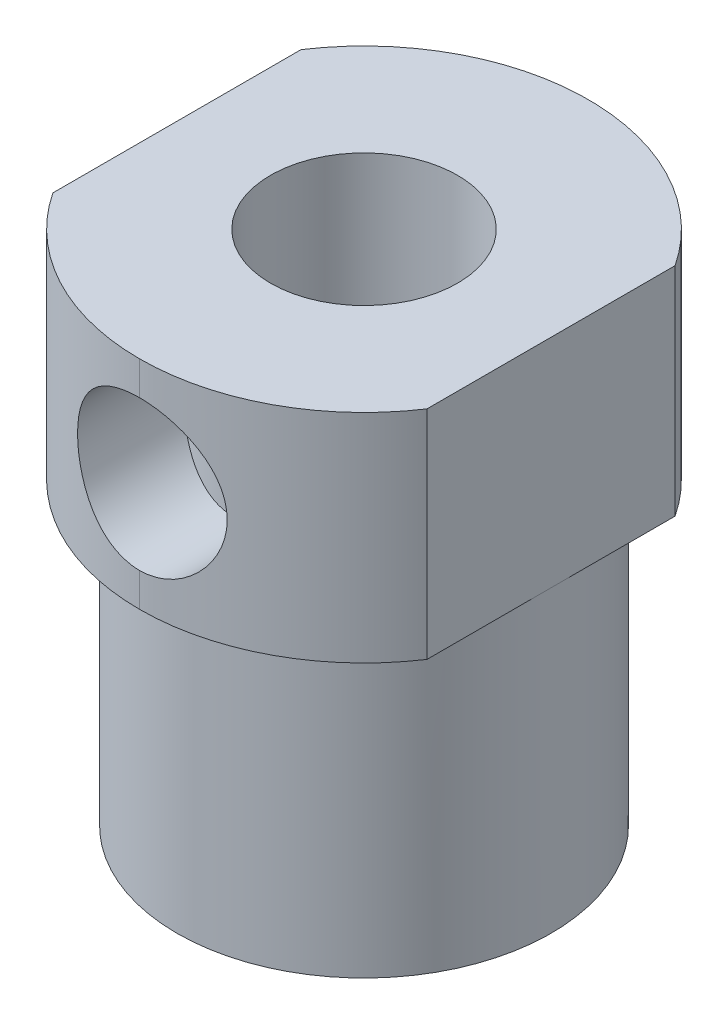
SolidWorks part; units mm, degrees
material "ABS"
ref_plane "Front Plane" through (0, 0, 0) normal (0, 0, 1) x (1, 0, 0)
ref_plane "Top Plane" through (0, 0, 0) normal (0, 1, 0) x (1, 0, 0)
ref_plane "Right Plane" through (0, 0, 0) normal (1, 0, 0) x (0, 0, -1)
sketch "Sketch4" plane through (0, 0, 0) normal (1, 0, 0) x (0, 0, -1)
  line L0 (-2.4, 0) -> (-2.4, 3)
  line L1 (-2.4, 3) -> (-0.75, 3)
  line L2 (-0.75, 3) -> (-0.75, 5)
  line L3 (-0.75, 5) -> (-2.5, 5)
  line L4 (-2.5, 5) -> (-2.5, 13.8)
  line L5 (-2.5, 13.8) -> (-6, 13.8)
  line L6 (-6, 13.8) -> (-6, 8)
  line L7 (-6, 8) -> (-5, 8)
  line L8 (-5, 8) -> (-5, 0)
  line L9 (-5, 0) -> (-2.4, 0)
  dimension "D1" = 3
  dimension "D2" = 2.4
  dimension "D3" = 5
  dimension "D4" = 0.75
  dimension "D5" = 8
  dimension "D6" = 6
  dimension "D7" = 5.8
  dimension "D8" = 2
  dimension "D9" = 2.5
sketch "Sketch2" plane through (0, 0, 0) normal (0, 1, 0) x (1, 0, 0)
  circle A0 centre (0, 0) radius 5
  dimension "D1" = 10
sweep "Sweep1" add profiles "Sketch4" path "Sketch2"
ref_plane "Plane1" through (0, 13.8, 6) normal (0, 0, 1) x (1, 0, 0)
sketch "Sketch5" plane through (0, 13.8, 6) normal (0, 0, 1) x (1, 0, 0)
  line L1 (0, 0) -> (0, -5.8) construction
  circle A0 centre (0, -2.9) radius 2
  dimension "D1" = 4
extrude "Cut-Extrude1" cut sketch "Sketch5" against normal offset from surface (3.1277 mm away) 1
sketch "Sketch7" plane through (0, 13.8, 0) normal (0, 1, 0) x (1, 0, 0)
  line L1 (-5, 6) -> (5, 6) construction
  line L2 (-5, 6) -> (-5, -6) construction
  line L3 (-5, -6) -> (5, -6) construction
  line L4 (5, 6) -> (5, -6) construction
  line L5 (-5, 6) -> (-6, 6)
  line L6 (-5, 6) -> (-5, -6)
  line L7 (-5, -6) -> (-6, -6)
  line L8 (-6, 6) -> (-6, -6)
  line L9 (5, 6) -> (6, 6)
  line L10 (5, 6) -> (5, -6)
  line L11 (5, -6) -> (6, -6)
  line L12 (6, 6) -> (6, -6)
  circle A0 centre (0, 0) radius 6 construction
  point P10 (0, 0)
  dimension "D1" = 5
  dimension "D2" = 5
extrude "Cut-Extrude2" cut sketch "Sketch7" against normal up to surface (5.8 mm away) up to face at (0, 8, 5.5)
